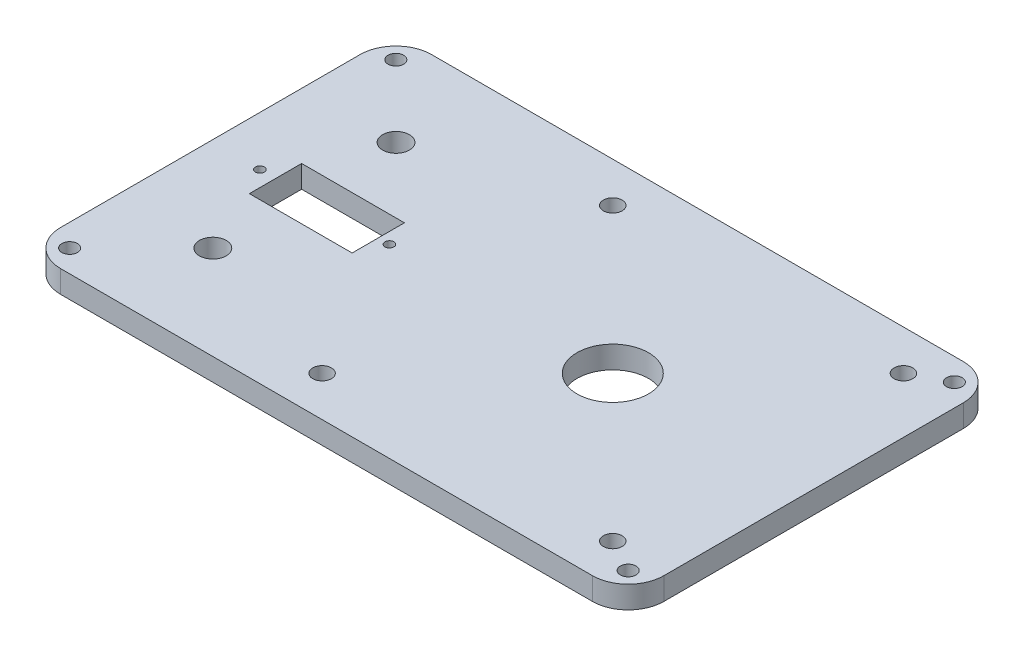
SolidWorks part; units mm, degrees
ref_plane "Front Plane" through (0, 0, 0) normal (0, 0, 1) x (1, 0, 0)
ref_plane "Top Plane" through (0, 0, 0) normal (0, 1, 0) x (1, 0, 0)
ref_plane "Right Plane" through (0, 0, 0) normal (1, 0, 0) x (0, 0, -1)
sketch "Sketch1" plane through (0, 0, 0) normal (0, 1, 0) x (1, 0, 0)
  line L0 (-67.5, 0) -> (67.5, 0) construction
  line L1 (67.5, -41.5) -> (-67.5, -41.5)
  line L2 (67.5, -41.5) -> (67.5, 41.5)
  line L3 (67.5, 41.5) -> (-67.5, 41.5)
  line L4 (-67.5, -41.5) -> (-67.5, 41.5)
  line L5 (67.5, -41.5) -> (-67.5, 41.5) construction
  line L6 (67.5, 41.5) -> (-67.5, -41.5) construction
  line L7 (22.55, 41.5) -> (22.55, -41.5) construction
  line L8 (49.455, -34.63) -> (-49.455, -34.63) construction
  line L9 (49.455, -34.63) -> (49.455, 34.63) construction
  line L10 (49.455, 34.63) -> (-49.455, 34.63) construction
  line L11 (-49.455, -34.63) -> (-49.455, 34.63) construction
  line L12 (49.455, -34.63) -> (-49.455, 34.63) construction
  line L13 (49.455, 34.63) -> (-49.455, -34.63) construction
  line L14 (0, 41.5) -> (0, -41.5) construction
  circle A0 centre (-9.98, 32.53) radius 2.1
  circle A1 centre (55.08, 32.53) radius 2.1
  circle A2 centre (55.08, -32.53) radius 2.1
  circle A3 centre (-9.98, -32.53) radius 2.1
  circle A4 centre (22.55, 0) radius 8
  circle A5 centre (-46.455, 20.5) radius 3
  circle A6 centre (-35.78, 0) radius 4.725
  circle A7 centre (-46.455, -20.5) radius 3
  circle A8 centre (-62.5, 36.5) radius 1.75
  circle A9 centre (62.5, 36.5) radius 1.75
  circle A10 centre (62.5, -36.5) radius 1.75
  circle A11 centre (-62.5, -36.5) radius 1.75
  point P0 (0, 0)
  point P13 (22.55, 0)
  point P18 (0, 0)
  point P27 (22.55, 0)
  point P43 (55.08, -32.53)
  dimension "D3" = 4.2
  dimension "D4" = 16
  dimension "D8" = 9.45
  dimension "D9" = 6
  dimension "D17" = 3.5
  dimension "D19" = 5
  dimension "D1" = 135
  dimension "D2" = 83
  dimension "D5" = 32.53
  dimension "D6" = 32.53
  dimension "D7" = 32.53
  dimension "D10" = 58.33
  dimension "D11" = 10.675
  dimension "D12" = 20.5
  dimension "D13" = 98.91
  dimension "D14" = 69.26
  dimension "D15" = 72.005
  dimension "D16" = 98.91
  dimension "D18" = 5
extrude "Boss-Extrude1" add sketch "Sketch1" along normal blind 5 contours A2 L2 A1 L3 L4 L1 A6 A5 A4 A3 A0 A7
sketch "Sketch3" plane through (0, 5, 0) normal (0, 1, 0) x (1, 0, 0)
  line L1 (-29.93, -5.85) -> (-52.93, -5.85)
  line L2 (-29.93, -5.85) -> (-29.93, 5.85)
  line L3 (-29.93, 5.85) -> (-52.93, 5.85)
  line L4 (-52.93, -5.85) -> (-52.93, 5.85)
  line L5 (-29.93, 0) -> (-41.63, 0) construction
  circle A2 centre (-35.78, 0) radius 5.85 construction
  circle A3 centre (-35.78, 0) radius 4.725 construction
  circle A4 centre (-27.43, 0) radius 1
  circle A5 centre (-56.43, 0) radius 1
  dimension "D3" = 11.7
  dimension "D2" = 2
  dimension "D5" = 2
  dimension "D1" = 23
  dimension "D4" = 2.5
  dimension "D6" = 3.5
extrude "Cut-Extrude1" cut sketch "Sketch3" against normal through all
sketch "Sketch4" plane through (0, 5, 0) normal (0, 1, 0) x (1, 0, 0)
  line L0 (-29.93, 5.85) -> (-52.93, 5.85) construction
  line L1 (-52.93, -5.85) -> (-29.93, -5.85) construction
  line L2 (-29.93, -5.85) -> (-29.93, 5.85) construction
  circle A0 centre (-35.78, 0) radius 5.85
  point P6 (-38.7653, 0)
fillet "Fillet1" radius 8 4 edges at (67.5, 2.5, -41.5) (-67.5, 2.5, -41.5) (-67.5, 2.5, 41.5) (67.5, 2.5, 41.5)
